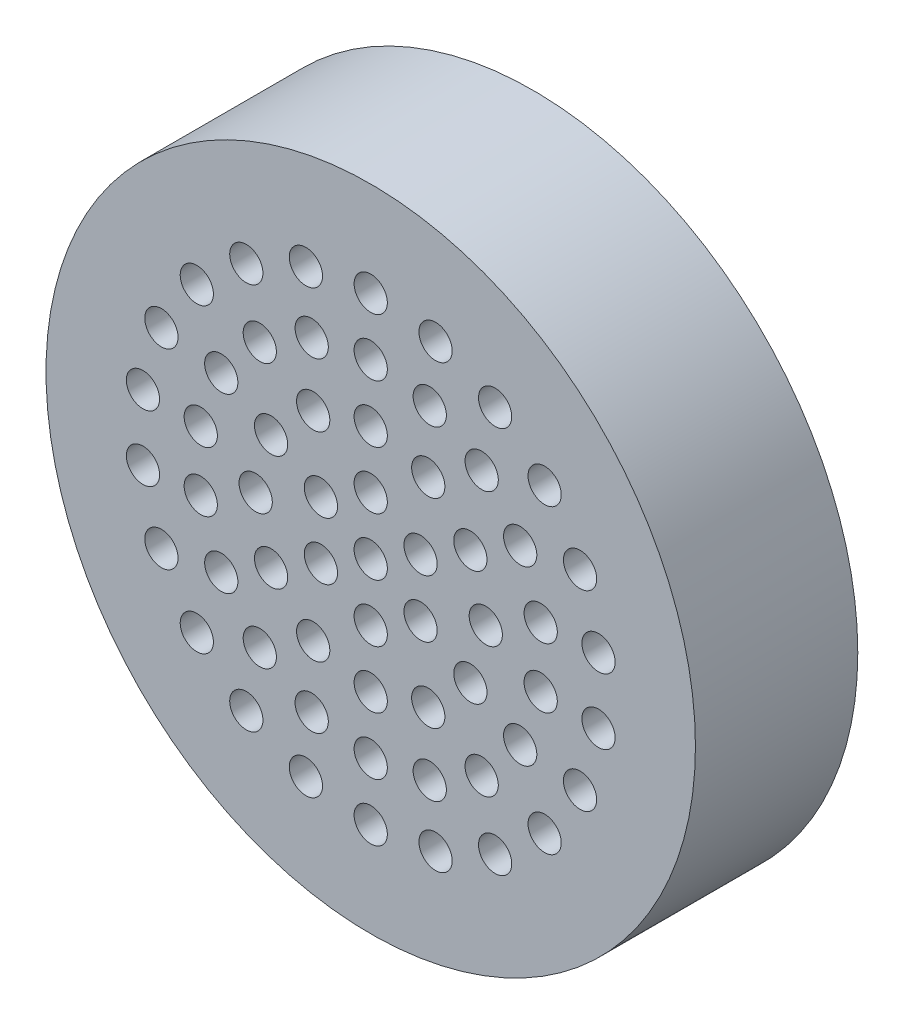
SolidWorks part; units mm, degrees
ref_plane "Plan de face" through (0, 0, 0) normal (0, 0, 1) x (1, 0, 0)
ref_plane "Plan de dessus" through (0, 0, 0) normal (0, 1, 0) x (1, 0, 0)
ref_plane "Plan de droite" through (0, 0, 0) normal (1, 0, 0) x (0, 0, -1)
sketch "Esquisse1" plane through (0, 0, 0) normal (0, 0, 1) x (1, 0, 0)
  circle A0 centre (0, 0) radius 25.4
extrude "Boss.-Extru.1" add sketch "Esquisse1" along normal blind 12.7
sketch "Esquisse2" plane through (0, 0, 0) normal (0, 0, -1) x (-1, 0, 0)
  circle A0 centre (0, 0) radius 1.3
  circle A1 centre (0, 4.5) radius 1.3
  circle A2 centre (0, 9) radius 1.3
  circle A3 centre (0, 13.5) radius 1.3
  circle A4 centre (0, 18) radius 1.3
  circle A5 centre (3.8971, 2.25) radius 1.3
  circle A6 centre (3.8971, -2.25) radius 1.3
  circle A7 centre (0, -4.5) radius 1.3
  circle A8 centre (-3.8971, -2.25) radius 1.3
  circle A9 centre (-3.8971, 2.25) radius 1.3
  circle A10 centre (4.5, 7.7942) radius 1.3
  circle A11 centre (7.7942, 4.5) radius 1.3
  circle A12 centre (9, 0) radius 1.3
  circle A13 centre (7.7942, -4.5) radius 1.3
  circle A14 centre (4.5, -7.7942) radius 1.3
  circle A15 centre (0, -9) radius 1.3
  circle A16 centre (-4.5, -7.7942) radius 1.3
  circle A17 centre (-7.7942, -4.5) radius 1.3
  circle A18 centre (-9, 0) radius 1.3
  circle A19 centre (-7.7942, 4.5) radius 1.3
  circle A20 centre (-4.5, 7.7942) radius 1.3
  circle A21 centre (4.6173, 12.6859) radius 1.3
  circle A22 centre (8.6776, 10.3416) radius 1.3
  circle A23 centre (11.6913, 6.75) radius 1.3
  circle A24 centre (13.2949, 2.3443) radius 1.3
  circle A25 centre (13.2949, -2.3443) radius 1.3
  circle A26 centre (11.6913, -6.75) radius 1.3
  circle A27 centre (8.6776, -10.3416) radius 1.3
  circle A28 centre (4.6173, -12.6859) radius 1.3
  circle A29 centre (0, -13.5) radius 1.3
  circle A30 centre (-4.6173, -12.6859) radius 1.3
  circle A31 centre (-8.6776, -10.3416) radius 1.3
  circle A32 centre (-11.6913, -6.75) radius 1.3
  circle A33 centre (-13.2949, -2.3443) radius 1.3
  circle A34 centre (-13.2949, 2.3443) radius 1.3
  circle A35 centre (-11.6913, 6.75) radius 1.3
  circle A36 centre (-8.6776, 10.3416) radius 1.3
  circle A37 centre (-4.6173, 12.6859) radius 1.3
  circle A38 centre (5.0712, 17.2709) radius 1.3
  circle A39 centre (9.7315, 15.1426) radius 1.3
  circle A40 centre (13.6035, 11.7875) radius 1.3
  circle A41 centre (16.3734, 7.4775) radius 1.3
  circle A42 centre (17.8168, 2.5617) radius 1.3
  circle A43 centre (17.8168, -2.5617) radius 1.3
  circle A44 centre (16.3734, -7.4775) radius 1.3
  circle A45 centre (13.6035, -11.7875) radius 1.3
  circle A46 centre (9.7315, -15.1426) radius 1.3
  circle A47 centre (5.0712, -17.2709) radius 1.3
  circle A48 centre (0, -18) radius 1.3
  circle A49 centre (-5.0712, -17.2709) radius 1.3
  circle A50 centre (-9.7315, -15.1426) radius 1.3
  circle A51 centre (-13.6035, -11.7875) radius 1.3
  circle A52 centre (-16.3734, -7.4775) radius 1.3
  circle A53 centre (-17.8168, -2.5617) radius 1.3
  circle A54 centre (-17.8168, 2.5617) radius 1.3
  circle A55 centre (-16.3734, 7.4775) radius 1.3
  circle A56 centre (-13.6035, 11.7875) radius 1.3
  circle A57 centre (-9.7315, 15.1426) radius 1.3
  circle A58 centre (-5.0712, 17.2709) radius 1.3
  point P24 (0, 0)
  point P46 (0, 0)
  point P81 (0, 0)
  point P124 (0, 0)
  dimension "D1" = 5
  dimension "D2" = 6
  dimension "D3" = 12
  dimension "D4" = 18
  dimension "D5" = 22
extrude "Enlèv. mat.-Extru.1" cut sketch "Esquisse2" against normal blind 12.7
